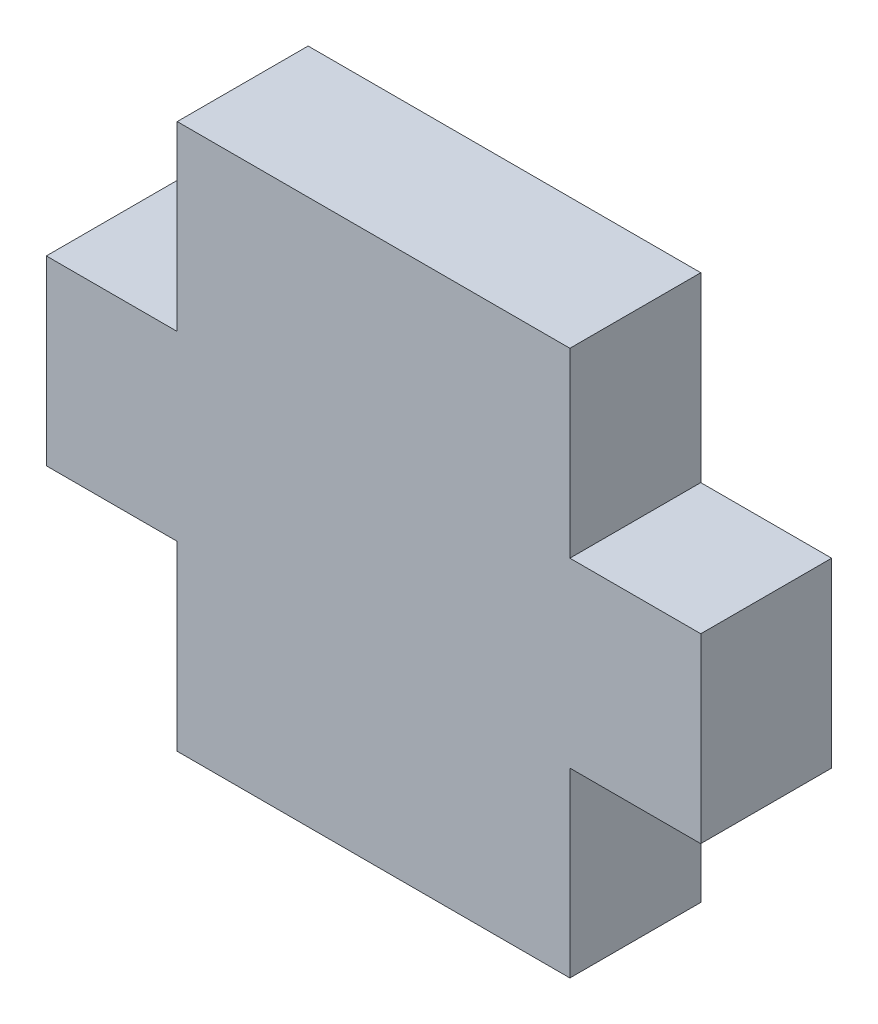
SolidWorks part; units mm, degrees
ref_plane "Front Plane" through (0, 0, 0) normal (0, 0, 1) x (1, 0, 0)
ref_plane "Top Plane" through (0, 0, 0) normal (0, 1, 0) x (1, 0, 0)
ref_plane "Right Plane" through (0, 0, 0) normal (1, 0, 0) x (0, 0, -1)
sketch "Sketch1" plane through (0, 0, 0) normal (0, 0, 1) x (1, 0, 0)
  line L1 (0, 0) -> (76.2, 0)
  line L2 (0, 0) -> (0, 63.5)
  line L3 (0, 63.5) -> (76.2, 63.5)
  line L4 (76.2, 0) -> (76.2, 63.5)
  dimension "D1" = 76.2
  dimension "D2" = 63.5
extrude "Boss-Extrude1" add sketch "Sketch1" along normal blind 15.24
sketch "Sketch2" plane through (0, 0, 15.24) normal (0, 0, 1) x (1, 0, 0)
  line L0 (76.2, 0) -> (76.2, 63.5) construction
  line L1 (0, 63.5) -> (15.24, 63.5)
  line L2 (0, 63.5) -> (0, 42.3333)
  line L3 (0, 42.3333) -> (15.24, 42.3333)
  line L4 (15.24, 63.5) -> (15.24, 42.3333)
  line L5 (0, 0) -> (15.24, 0)
  line L6 (0, 0) -> (0, 21.1667)
  line L7 (0, 21.1667) -> (15.24, 21.1667)
  line L8 (15.24, 0) -> (15.24, 21.1667)
  line L9 (76.2, 63.5) -> (60.96, 63.5)
  line L10 (76.2, 63.5) -> (76.2, 42.3333)
  line L11 (76.2, 42.3333) -> (60.96, 42.3333)
  line L12 (60.96, 63.5) -> (60.96, 42.3333)
  line L13 (76.2, 21.1667) -> (60.96, 21.1667)
  line L14 (76.2, 21.1667) -> (76.2, 0)
  line L15 (76.2, 0) -> (60.96, 0)
  line L16 (60.96, 21.1667) -> (60.96, 0)
  line L17 (0, 0) -> (76.2, 0) construction
  line L18 (15.24, 42.3333) -> (15.24, 21.1667) construction
  line L19 (60.96, 42.3333) -> (60.96, 21.1667) construction
  dimension "D1" = 15.24
  dimension "D2" = 15.24
extrude "Cut-Extrude1" cut sketch "Sketch2" against normal blind 15.24
equation "\"Foamcore\"= .1"
equation "\"MDF\"= .6"
equation "\"GMaterial\"= \"MDF\""
equation "\"D1@Boss-Extrude1\"=\"GMaterial\""
equation "\"D1@Cut-Extrude2\"=\"GMaterial\""
equation "\"D1@Sketch2\"=\"GMaterial\""
equation "\"D2@Sketch2\"=\"GMaterial\""
equation "\"D1@Cut-Extrude1\"=\"GMaterial\""
